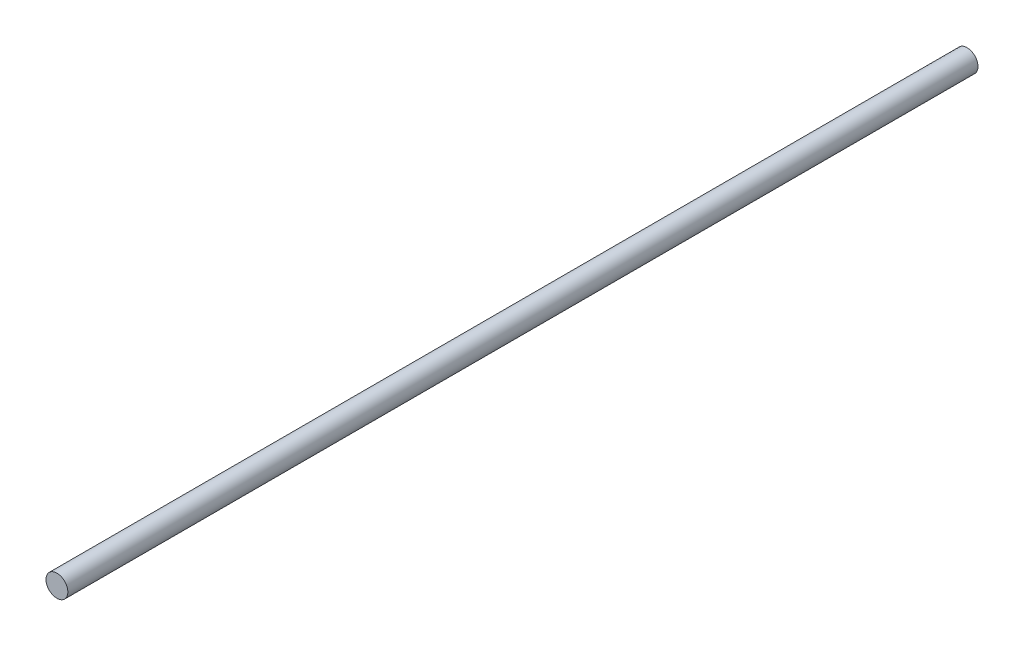
SolidWorks part; units mm, degrees
material "普通碳钢"
ref_plane "前视基准面" through (0, 0, 0) normal (0, 0, 1) x (1, 0, 0)
ref_plane "上视基准面" through (0, 0, 0) normal (0, 1, 0) x (1, 0, 0)
ref_plane "右视基准面" through (0, 0, 0) normal (1, 0, 0) x (0, 0, -1)
sketch "草图1" plane through (0, 0, 0) normal (0, 0, 1) x (1, 0, 0)
  circle A0 centre (0, 0) radius 3
  dimension "D1" = 6
extrude "凸台-拉伸1" add sketch "草图1" along normal blind 250
